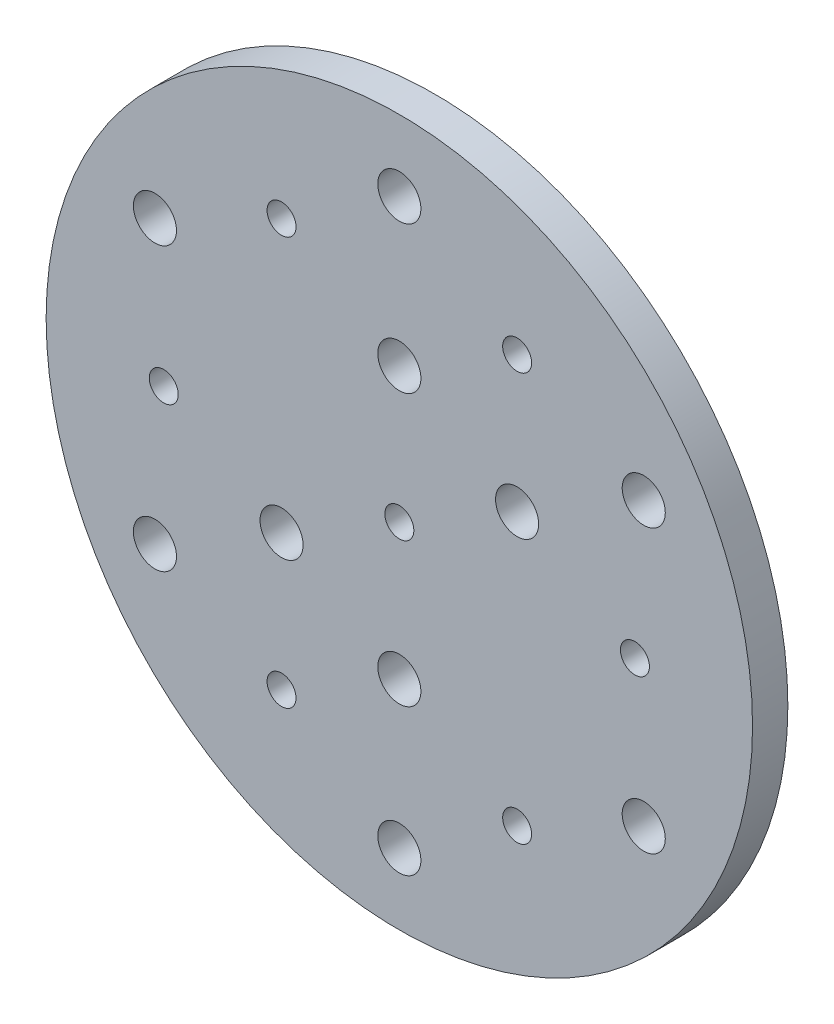
SolidWorks part; units mm, degrees
ref_plane "Plan de face" through (0, 0, 0) normal (0, 0, 1) x (1, 0, 0)
ref_plane "Plan de dessus" through (0, 0, 0) normal (0, 1, 0) x (1, 0, 0)
ref_plane "Plan de droite" through (0, 0, 0) normal (1, 0, 0) x (0, 0, -1)
sketch "Esquisse1" plane through (0, 0, 0) normal (0, 0, 1) x (1, 0, 0)
  line L0 (53.6751, 0) -> (-86.559, 0) construction
  line L1 (0, 50) -> (0, -56.2363) construction
  line L2 (0, 0) -> (70.5826, 40.7509) construction
  line L3 (0, 0) -> (-77.9761, 45.0195) construction
  circle A0 centre (0, 0) radius 50
  circle A1 centre (33.35, 0) radius 16.65 construction
  circle A2 centre (16.675, -28.8819) radius 16.65 construction
  circle A3 centre (-16.675, -28.8819) radius 16.65 construction
  circle A4 centre (-33.35, 0) radius 16.65 construction
  circle A5 centre (-16.675, 28.8819) radius 16.65 construction
  circle A6 centre (16.675, 28.8819) radius 16.65 construction
  circle A7 centre (-34.5978, 19.9751) radius 3.05
  circle A8 centre (0, 39.9502) radius 3.05
  circle A9 centre (34.5978, 19.9751) radius 3.05
  circle A10 centre (34.5978, -19.9751) radius 3.05
  circle A11 centre (0, -39.9502) radius 3.05
  circle A12 centre (-34.5978, -19.9751) radius 3.05
  circle A13 centre (0, 19.1653) radius 3.05
  circle A14 centre (0, 0) radius 16.65 construction
  circle A15 centre (0, -19.2328) radius 3.05
  circle A16 centre (-33.35, 0) radius 2.05
  circle A17 centre (-16.675, 28.8819) radius 2.05
  circle A18 centre (16.675, 28.8819) radius 2.05
  circle A19 centre (33.35, 0) radius 2.05
  circle A20 centre (16.675, -28.8819) radius 2.05
  circle A21 centre (-16.675, -28.8819) radius 2.05
  circle A22 centre (0, 0) radius 2.05
  circle A23 centre (-16.6714, -9.6252) radius 3.05
  circle A24 centre (16.6696, 9.6242) radius 3.05
  point P20 (0, 0)
  point P30 (0, 0)
  point P54 (0, 0)
  point P59 (-16.675, -9.6252)
  point P60 (16.675, 9.6242)
  dimension "D1" = 6
  dimension "D2" = 30
  dimension "D4" = 6
  dimension "D5" = 6
  dimension "D3" = 30
extrude "Boss.-Extru.1" add sketch "Esquisse1" along normal blind 5
